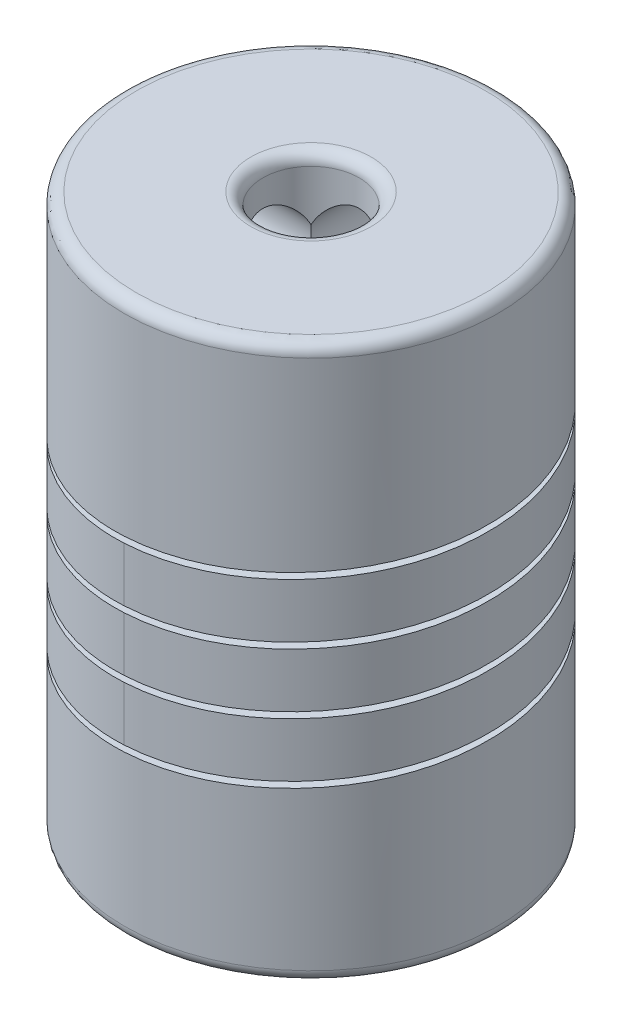
SolidWorks part; units mm, degrees
material "Cast Alloy Steel"
ref_plane "Front Plane" through (0, 0, 0) normal (0, 0, 1) x (1, 0, 0)
ref_plane "Top Plane" through (0, 0, 0) normal (0, 1, 0) x (1, 0, 0)
ref_plane "Right Plane" through (0, 0, 0) normal (1, 0, 0) x (0, 0, -1)
sketch "Sketch1" plane through (0, 0, 0) normal (0, 1, 0) x (1, 0, 0)
  circle A0 centre (0, 0) radius 7.75
  dimension "D1" = 15.5
extrude "Boss-Extrude1" add sketch "Sketch1" along normal mid plane 23
sketch "Sketch2" plane through (0, 11.5, 0) normal (0, 1, 0) x (1, 0, 0)
  circle A0 centre (0, 0) radius 2
  dimension "D1" = 4
extrude "Cut-Extrude1" cut sketch "Sketch2" against normal blind 6
sketch "Sketch12" plane through (0, -11.5, 0) normal (0, -1, 0) x (1, 0, 0)
  circle A0 centre (0, 0) radius 3
  dimension "D1" = 6
extrude "Cut-Extrude3" cut sketch "Sketch12" against normal up to surface (17 mm away) up to face at (0, 5.5, 2)
ref_plane "Plane1" through (-7.75, 0, 0) normal (-1, 0, 0) x (0, 0, 1)
sketch "Sketch3" plane through (-7.75, 0, 0) normal (-1, 0, 0) x (0, 0, 1)
  line L0 (-40.9988, 0) -> (47.9686, 0) construction
  circle A0 centre (0, 8.4) radius 1.5
  circle A1 centre (0, -8.4) radius 1.5
  dimension "D1" = 8.4
  dimension "D2" = 3
extrude "Cut-Extrude2" cut sketch "Sketch3" against normal up to surface (6.4271 mm away)
fillet "Fillet1" radius 0.5 2 edges at (0, 11.5, 7.75) (0, -11.5, 7.75)
fillet "Fillet3" radius 0.25 2 edges at (-7.6099, -8.0861, -1.4668) (-7.6099, 8.7139, -1.4668)
ref_plane "Plane2" through (0, -5, 0) normal (0, -1, 0) x (-1, 0, 0)
sketch "Sketch7" plane through (0, -5, 0) normal (0, -1, 0) x (-1, 0, 0)
  circle A0 centre (0, 0) radius 9.5211
curve "Helix/Spiral2" pitch 2.5 height 10 turns 4
sketch "Sketch8" plane through (0, 0, 0) normal (0, 0, 1) x (1, 0, 0)
  line L0 (-7.75, 6.65) -> (-7.75, -6.65) construction
  line L1 (-13.5, -2.6216) -> (-2, -2.6216)
  line L2 (-13.5, -2.6216) -> (-13.5, -2.8716)
  line L3 (-13.5, -2.8716) -> (-2, -2.8716)
  line L4 (-2, -2.6216) -> (-2, -2.8716)
  line L5 (-13.5, -2.6216) -> (-2, -2.8716) construction
  line L6 (-13.5, -2.8716) -> (-2, -2.6216) construction
  spline S0 degree 3 poles (-9.5211, -5) (-9.5211, -4.9483) (-9.0254, -4.8436) (-6.9077, -4.6875) (-3.7384, -4.5312) (0, -4.375) (3.7384, -4.2187) (6.9077, -4.0625) (9.0254, -3.9062) (9.769, -3.75) (9.0254, -3.5937) (6.9077, -3.4375) (3.7384, -3.2812) (0, -3.125) (-3.7384, -2.9687) (-6.9077, -2.8125) (-9.0254, -2.6562) (-9.769, -2.5) (-9.0254, -2.3437) (-6.9077, -2.1875) (-3.7384, -2.0312) (0, -1.875) (3.7384, -1.7187) (6.9077, -1.5625) (9.0254, -1.4062) (9.769, -1.25) (9.0254, -1.0937) (6.9077, -0.9375) (3.7384, -0.7812) (0, -0.625) (-3.7384, -0.4687) (-6.9077, -0.3125) (-9.0254, -0.1562) (-9.769, 0) (-9.0254, 0.1563) (-6.9077, 0.3125) (-3.7384, 0.4688) (0, 0.625) (3.7384, 0.7813) (6.9077, 0.9375) (9.0254, 1.0938) (9.769, 1.25) (9.0254, 1.4063) (6.9077, 1.5625) (3.7384, 1.7188) (0, 1.875) (-3.7384, 2.0312) (-6.9077, 2.1875) (-9.0254, 2.3437) (-9.769, 2.5) (-9.0254, 2.6562) (-6.9077, 2.8125) (-3.7384, 2.9687) (0, 3.125) (3.7384, 3.2812) (6.9077, 3.4375) (9.0254, 3.5937) (9.769, 3.75) (9.0254, 3.9062) (6.9077, 4.0625) (3.7384, 4.2187) (0, 4.375) (-3.7384, 4.5312) (-6.9077, 4.6875) (-9.0254, 4.8436) (-9.5211, 4.9483) (-9.5211, 5) knots 0 0 0 0 0.015625 0.03125 0.046875 0.0625 0.078125 0.09375 0.109375 0.125 0.140625 0.15625 0.171875 0.1875 0.203125 0.21875 0.234375 0.25 0.265625 0.28125 0.296875 0.3125 0.328125 0.34375 0.359375 0.375 0.390625 0.40625 0.421875 0.4375 0.453125 0.46875 0.484375 0.5 0.515625 0.53125 0.546875 0.5625 0.578125 0.59375 0.609375 0.625 0.640625 0.65625 0.671875 0.6875 0.703125 0.71875 0.734375 0.75 0.765625 0.78125 0.796875 0.8125 0.828125 0.84375 0.859375 0.875 0.890625 0.90625 0.921875 0.9375 0.953125 0.96875 0.984375 1 1 1 1 construction
  point P0 (-7.75, -2.7466)
  dimension "D1" = 0.25
  dimension "D2" = 2
sweep "Cut-Sweep2" cut profiles "Sketch8" path "Helix/Spiral2"
pattern_circular "CirPattern1" count 2 over 90 about axis through (0, 11, 0) along (0, 1, 0) of "Cut-Extrude2", "Fillet3"
fillet "Fillet4" radius 0.5 2 edges at (0, -11.5, -3) (0, 11.5, 2)
